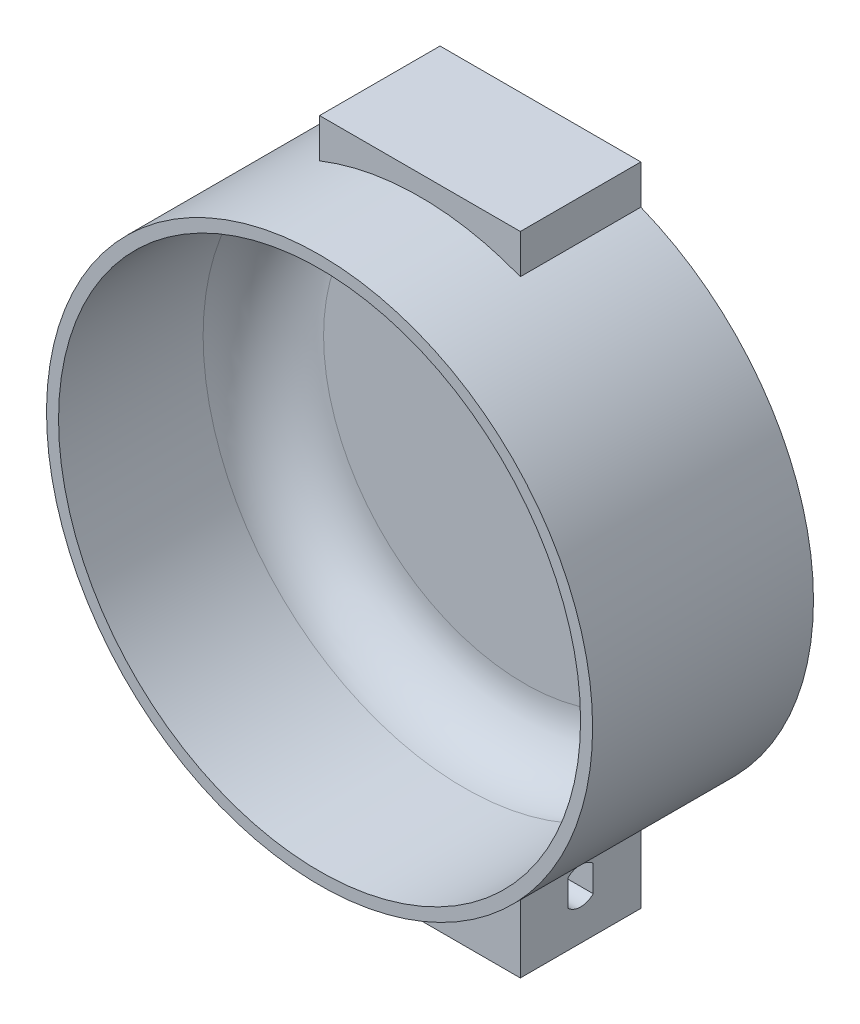
SolidWorks part; units mm, degrees
ref_plane "前视基准面" through (0, 0, 0) normal (0, 0, 1) x (1, 0, 0)
ref_plane "上视基准面" through (0, 0, 0) normal (0, 1, 0) x (1, 0, 0)
ref_plane "右视基准面" through (0, 0, 0) normal (1, 0, 0) x (0, 0, -1)
other "Configuration Table"
sketch "草图1" plane through (0, 0, 0) normal (0, 0, 1) x (1, 0, 0)
  circle A0 centre (0, 0) radius 65
  dimension "D1" = 130
extrude "拉伸-薄壁1" add sketch "草图1" along normal blind 55 thin
sketch "草图2" plane through (0, 0, 0) normal (0, 0, -1) x (-1, 0, 0)
  circle A1 centre (0, 0) radius 68
  circle A2 centre (0, 0) radius 68
  dimension "D1" = 0
extrude "凸台-拉伸1" add sketch "草图2" against normal blind 4
fillet "圆角1" radius 15 1 edges at (-65, 0, 4)
sketch "草图3" plane through (0, 0, 0) normal (0, 0, -1) x (-1, 0, 0)
  line L0 (0, 68) -> (0, -68)
  line L1 (-68, 0) -> (68, 0)
  line L2 (-25, 73) -> (25, 73)
  line L3 (-25, 73) -> (-25, 63)
  line L4 (-25, 63) -> (25, 63)
  line L5 (25, 73) -> (25, 63)
  line L6 (-25, 73) -> (25, 63) construction
  line L7 (-25, 63) -> (25, 73) construction
  line L8 (-25, -63) -> (25, -63)
  line L9 (25, -73) -> (25, -63)
  line L10 (-25, -73) -> (25, -73)
  line L11 (-25, -73) -> (-25, -63)
  circle A0 centre (0, 0) radius 68 construction
  circle A2 centre (0, 0) radius 68
  circle A3 centre (0, 0) radius 68
  circle M7 centre (0, 0) radius 68
  dimension "D1" = 50
  dimension "D2" = 10
  dimension "D3" = 0
extrude "凸台-拉伸2" add sketch "草图3" against normal blind 30 contours L11 L10 L9 M7 | L5 L2 L3 M7
sketch "草图4" plane through (0, -73, 0) normal (0, -1, 0) x (1, 0, 0)
  line L4 (-25, 0) -> (25, 0)
  line L5 (25, 0) -> (25, 30)
  line L6 (25, 30) -> (-25, 30)
  line L7 (-25, 30) -> (-25, 0)
  line L8 (-25, 0) -> (25, 0)
  line L9 (25, 0) -> (25, 30)
  line L10 (25, 30) -> (-25, 30)
  line L11 (-25, 30) -> (-25, 0)
  dimension "D1" = 0
extrude "凸台-拉伸3" add sketch "草图4" along normal blind 15
sketch "草图5" plane through (25, 0, 0) normal (1, 0, 0) x (0, 0, -1)
  line L0 (-30, -75.6188) -> (0, -75.6188)
  line L1 (-30, -88) -> (-30, -63.2376) construction
  line L2 (0, -88) -> (0, -63.2376) construction
  line L4 (-18.15, -69.3608) -> (-11.85, -69.3608)
  line L5 (-18.15, -69.3608) -> (-18.15, -81.8769)
  line L6 (-18.15, -81.8769) -> (-11.85, -81.8769)
  line L7 (-11.85, -69.3608) -> (-11.85, -81.8769)
  line L8 (-18.15, -69.3608) -> (-11.85, -81.8769) construction
  line L9 (-18.15, -81.8769) -> (-11.85, -69.3608) construction
  circle A0 centre (-98.7011, -47.3907) radius 5.1445
  circle A1 centre (-15, -75.6188) radius 4.55
  dimension "D1" = 9.1
  dimension "D2" = 6.3
extrude "切除-拉伸1" cut sketch "草图5" against normal blind 40 contours L7 A1 L5 L0 | L5 A1 L7 L0
sketch "草图6" plane through (0, 0, 18.15) normal (0, 0, -1) x (-1, 0, 0)
  line L0 (-25, -75.6188) -> (15.1394, -75.6188)
  line L1 (-25, -72.3355) -> (-25, -78.9021) construction
  circle A0 centre (4.9682, -75.6188) radius 2.8
  dimension "D1" = 5.6
extrude "切除-拉伸2" cut sketch "草图6" against normal blind 20 and the other way blind 10 contours L0 A0 | L0 A0
